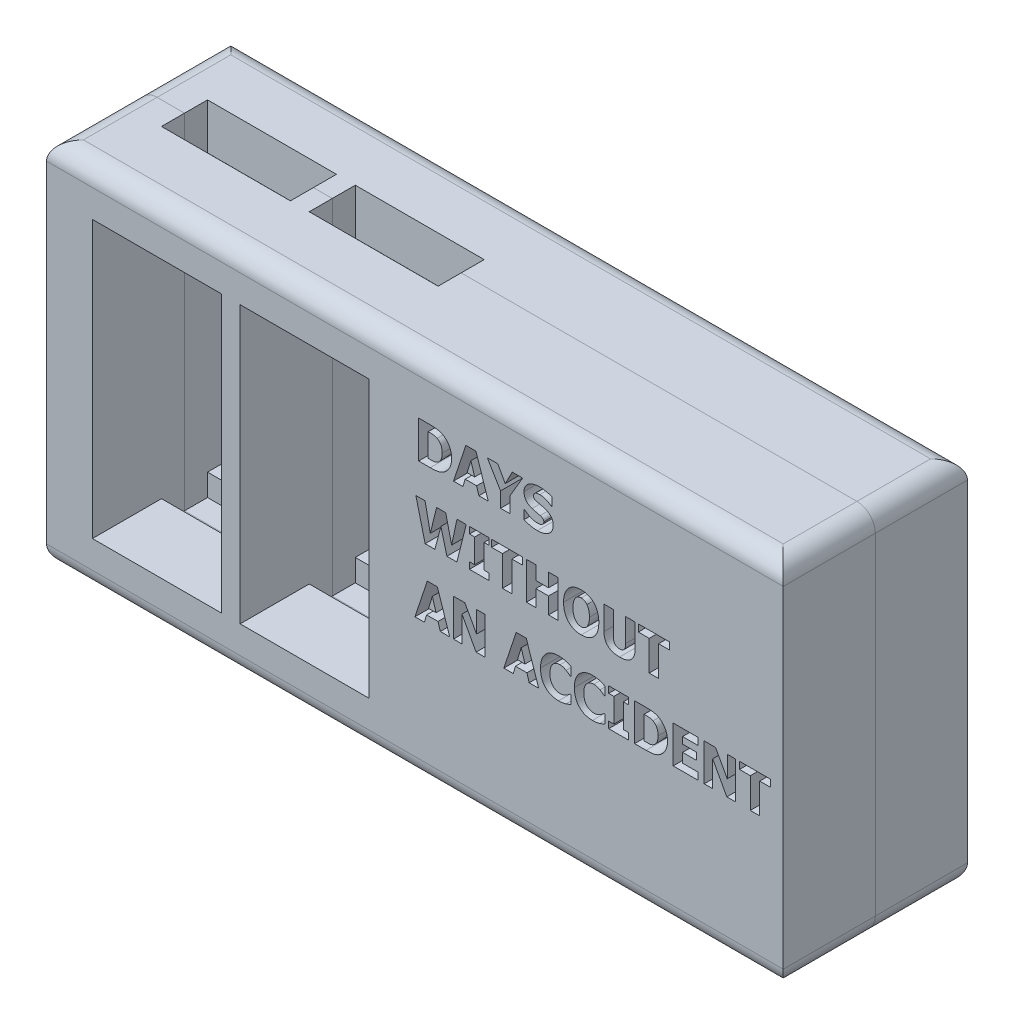
SolidWorks part; units mm, degrees
ref_plane "Front Plane" through (0, 0, 0) normal (0, 0, 1) x (1, 0, 0)
ref_plane "Top Plane" through (0, 0, 0) normal (0, 1, 0) x (1, 0, 0)
ref_plane "Right Plane" through (0, 0, 0) normal (1, 0, 0) x (0, 0, -1)
sketch "Sketch1" plane through (0, 0, 0) normal (0, 1, 0) x (1, 0, 0)
  line L1 (0, 0) -> (101.6, 0)
  line L2 (0, 0) -> (0, 25.4)
  line L3 (0, 25.4) -> (101.6, 25.4)
  line L4 (101.6, 0) -> (101.6, 25.4)
  dimension "D1" = 101.6
  dimension "D2" = 25.4
extrude "Boss-Extrude1" add sketch "Sketch1" along normal blind 50.8
sketch "Sketch2" plane through (0, 0, 0) normal (0, 0, 1) x (1, 0, 0)
  line L0 (50.8, 50.8) -> (50.8, 0) construction
  line L1 (0, 50.8) -> (101.6, 50.8) construction
  line L2 (0, 0) -> (101.6, 0) construction
  line L3 (0, 25.4) -> (101.6, 25.4) construction
  line L4 (0, 50.8) -> (0, 0) construction
  line L5 (101.6, 50.8) -> (101.6, 0) construction
  line L6 (12.7, 50.8) -> (12.7, 0) construction
  line L7 (25.4, 50.8) -> (25.4, 0) construction
  line L8 (38.1, 50.8) -> (38.1, 0) construction
  line L9 (0, 6.3612) -> (50.8, 6.3612) construction
  line L10 (0, 12.7112) -> (50.8, 12.7112) construction
  line L11 (0, 19.0612) -> (50.8, 19.0612) construction
  line L12 (0, 25.4112) -> (50.8, 25.4112) construction
  line L13 (0, 31.7612) -> (50.8, 31.7612) construction
  line L14 (0, 38.1112) -> (50.8, 38.1112) construction
  line L15 (0, 44.4612) -> (50.8, 44.4612) construction
  line L16 (26.6988, 44.4612) -> (44.4788, 44.4612)
  line L17 (24.1012, 6.3388) -> (6.3212, 6.3388)
  line L18 (24.1012, 6.3388) -> (24.1012, 44.4612)
  line L19 (24.1012, 44.4612) -> (6.3212, 44.4612)
  line L20 (6.3212, 6.3388) -> (6.3212, 44.4612)
  line L21 (24.1012, 6.3388) -> (6.3212, 44.4612) construction
  line L22 (24.1012, 44.4612) -> (6.3212, 6.3388) construction
  line L23 (44.4788, 6.3388) -> (44.4788, 44.4612)
  line L24 (26.6988, 6.3388) -> (44.4788, 6.3388)
  line L25 (26.6988, 6.3388) -> (26.6988, 44.4612)
  point P21 (15.2112, 25.4)
  dimension "D1" = 12.7
  dimension "D2" = 3
  dimension "D3" = 12.7
  dimension "D4" = 6.3612
  dimension "D5" = 7
  dimension "D6" = 6.35
  dimension "D7" = 17.78
  dimension "D8" = 6.3212
extrude "Cut-Extrude1" cut sketch "Sketch2" against normal blind 20.32
sketch "Sketch5" plane through (0, 0, 0) normal (0, 0, 1) x (1, 0, 0)
  line L0 (50.8, 50.8) -> (50.8, 0) construction
  line L1 (0, 50.8) -> (101.6, 50.8) construction
  line L2 (0, 0) -> (101.6, 0) construction
  line L3 (50.8, 0) -> (101.6, 0) construction
  line L4 (63.5, 50.8) -> (63.5, 0) construction
  line L5 (76.2, 50.8) -> (76.2, 0) construction
  line L6 (88.9, 50.8) -> (88.9, 0) construction
  line L7 (101.6, 50.8) -> (101.6, 0) construction
  line L8 (50.8, 6.35) -> (101.6, 6.35) construction
  line L9 (50.8, 12.7) -> (101.6, 12.7) construction
  line L10 (50.8, 19.05) -> (101.6, 19.05) construction
  line L11 (50.8, 25.4) -> (101.6, 25.4) construction
  line L12 (50.8, 31.75) -> (101.6, 31.75) construction
  line L13 (50.8, 38.1) -> (101.6, 38.1) construction
  line L14 (50.8, 44.45) -> (101.6, 44.45) construction
  line L15 (50.8, 50.8) -> (101.6, 50.8) construction
  text T0 "DAYS \r\nWITHOUT\r\nAN ACCIDENT\r\n" font "Tahoma" height in points 19
  dimension "D3" = 12.7
  dimension "D4" = 6.35
  dimension "D5" = 2.54
  dimension "D6" = 31.75
  dimension "D1" = 5
  dimension "D2" = 9
extrude "Cut-Extrude2" cut sketch "Sketch5" against normal blind 10.16
sketch "Sketch6" plane through (0, 50.8, 0) normal (0, 1, 0) x (1, 0, 0)
  line L0 (0, 12.7) -> (101.6, 12.7) construction
  line L1 (0, 25.4) -> (0, 0) construction
  line L2 (101.6, 0) -> (101.6, 25.4) construction
  line L3 (50.8, 25.4) -> (50.8, 0) construction
  line L4 (101.6, 25.4) -> (0, 25.4) construction
  line L5 (0, 0) -> (101.6, 0) construction
  line L6 (15.2112, 20.32) -> (15.2112, 0) construction
  line L7 (24.1012, 20.32) -> (6.3212, 20.32) construction
  line L8 (15.2112, 0) -> (15.2112, 25.4) construction
  line L9 (35.5888, 20.32) -> (35.5888, 0) construction
  line L10 (44.4788, 20.32) -> (26.6988, 20.32) construction
  line L11 (35.5888, 0) -> (35.5888, 25.4) construction
  line L12 (24.1012, 20.32) -> (26.6988, 20.32) construction
  line L13 (25.4, 20.32) -> (25.4, 0) construction
  line L14 (25.4, 0) -> (25.4, 25.4) construction
  line L15 (24.1012, 20.32) -> (25.4, 20.32) construction
  line L16 (24.1012, 20.32) -> (24.1012, 25.4) construction
  line L17 (24.1012, 25.4) -> (24.1012, 0) construction
  line L19 (26.6988, 25.4) -> (26.6988, 0) construction
  line L20 (26.6988, 20.32) -> (26.6988, 25.4) construction
  line L21 (44.4788, 15.875) -> (26.6988, 15.875)
  line L22 (6.3212, 9.525) -> (24.1012, 9.525)
  line L23 (6.3212, 9.525) -> (6.3212, 15.875)
  line L24 (6.3212, 15.875) -> (24.1012, 15.875)
  line L25 (24.1012, 9.525) -> (24.1012, 15.875)
  line L26 (6.3212, 9.525) -> (24.1012, 15.875) construction
  line L27 (6.3212, 15.875) -> (24.1012, 9.525) construction
  line L28 (26.6988, 9.525) -> (26.6988, 15.875)
  line L29 (44.4788, 9.525) -> (26.6988, 9.525)
  line L30 (44.4788, 9.525) -> (44.4788, 15.875)
  line L31 (6.3212, 20.32) -> (6.3212, 0) construction
  point P37 (15.2112, 12.7)
  dimension "D1" = 0
  dimension "D2" = 6.35
extrude "Cut-Extrude3" cut sketch "Sketch6" against normal blind 47.498
fillet "Fillet2" radius 2.54 8 edges at (50.8, 0, -25.4) (50.8, 50.8, -25.4) (101.6, 50.8, -12.7) (101.6, 0, -12.7) (50.8, 50.8, 0) (0, 50.8, -12.7) (0, 0, -12.7) (50.8, 0, 0)
ref_plane "Plane1" through (0, 27.94, 0) normal (0, 1, 0) x (1, 0, 0)
ref_plane "Plane2" through (0, 0, -12.7) normal (0, 0, 1) x (1, 0, 0)
split "Split1" trim tools "Plane2" bodies to split 104 resulting bodies 121 122
